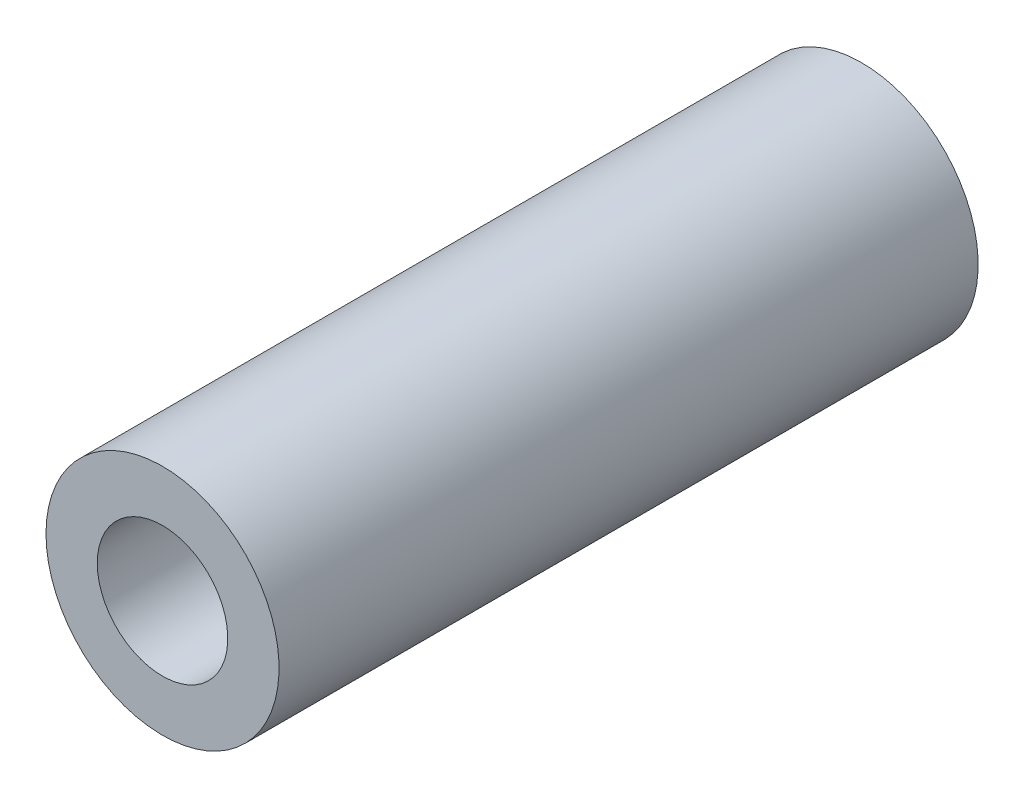
SolidWorks part; units mm, degrees
ref_plane "Front Plane" through (0, 0, 0) normal (0, 0, 1) x (1, 0, 0)
ref_plane "Top Plane" through (0, 0, 0) normal (0, 1, 0) x (1, 0, 0)
ref_plane "Right Plane" through (0, 0, 0) normal (1, 0, 0) x (0, 0, -1)
sketch "Sketch1" plane through (0, 0, 0) normal (0, 0, 1) x (1, 0, 0)
  circle A0 centre (0, 0) radius 3.175
  circle A1 centre (0, 0) radius 1.778
  dimension "OD" = 6.35
  dimension "ID" = 3.556
extrude "Extrude1" add sketch "Sketch1" along normal mid plane 19.05
sketch "Sketch2" plane through (0, 0, 0) normal (1, 0, 0) x (0, 0, -1)
  line L0 (-9.525, -1.778) -> (9.525, -1.778) construction
  line L3 (9.525, 1.778) -> (-9.525, 1.778) construction
  line L5 (-9.525, -1.778) -> (9.525, -1.778)
  line L6 (9.525, 1.778) -> (-9.525, 1.778)
sketch "Sketch4" plane through (0, 0, 9.525) normal (0, 0, 1) x (1, 0, 0)
  line L0 (0, 0) -> (-1.2572, 1.2572)
  line L1 (0, -2.6194) -> (0, 2.6194) construction
  circle A0 centre (0, 0) radius 1.778 construction
  dimension "D1" = 45
